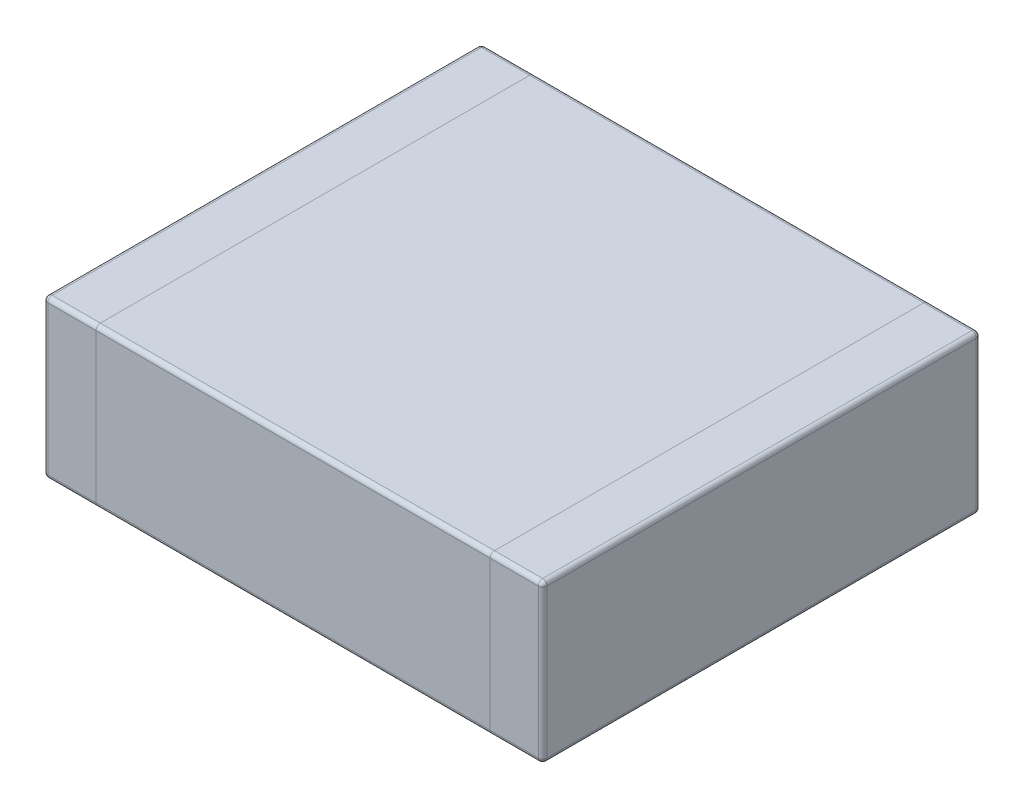
SolidWorks part; units mm, degrees
ref_plane "Front Plane" through (0, 0, 0) normal (0, 0, 1) x (1, 0, 0)
ref_plane "Top Plane" through (0, 0, 0) normal (0, 1, 0) x (1, 0, 0)
ref_plane "Right Plane" through (0, 0, 0) normal (1, 0, 0) x (0, 0, -1)
sketch "Sketch1" plane through (0, 0, 0) normal (0, 1, 0) x (1, 0, 0)
  line L1 (-2.85, -2.5) -> (2.85, -2.5)
  line L2 (-2.85, -2.5) -> (-2.85, 2.5)
  line L3 (-2.85, 2.5) -> (2.85, 2.5)
  line L4 (2.85, -2.5) -> (2.85, 2.5)
  line L5 (-2.85, -2.5) -> (2.85, 2.5) construction
  line L6 (-2.85, 2.5) -> (2.85, -2.5) construction
  point P0 (0, 0)
  dimension "D1" = 5.7
  dimension "D2" = 5
extrude "Extrude1" add sketch "Sketch1" along normal blind 1.8
fillet "Fillet1" radius 0.05 12 edges at (2.85, 0.9, -2.5) (-2.85, 0.9, -2.5) (-2.85, 0.9, 2.5) (2.85, 0.9, 2.5) (0, 1.8, 2.5) (-2.85, 1.8, 0) (0, 1.8, -2.5) (2.85, 1.8, 0) (0, 0, -2.5) (-2.85, 0, 0) (0, 0, 2.5) (2.85, 0, 0)
sketch "Sketch2" plane through (0, 0, 0) normal (0, 1, 0) x (1, 0, 0)
  line L0 (-2.8, 2.5) -> (2.8, 2.5) construction
  line L1 (-2.25, -2.5) -> (2.25, -2.5)
  line L2 (-2.25, -2.5) -> (-2.25, 2.5)
  line L3 (-2.25, 2.5) -> (2.25, 2.5)
  line L4 (2.25, -2.5) -> (2.25, 2.5)
  line L5 (2.8, -2.5) -> (-2.8, -2.5) construction
  line L6 (0, 2.45) -> (0, -0.6635) construction
  line L7 (2.8, 2.45) -> (-2.8, 2.45) construction
  line L9 (-2.85, -2.45) -> (-2.85, 2.45) construction
  dimension "D1" = 0.6
split line "Split Line3"
